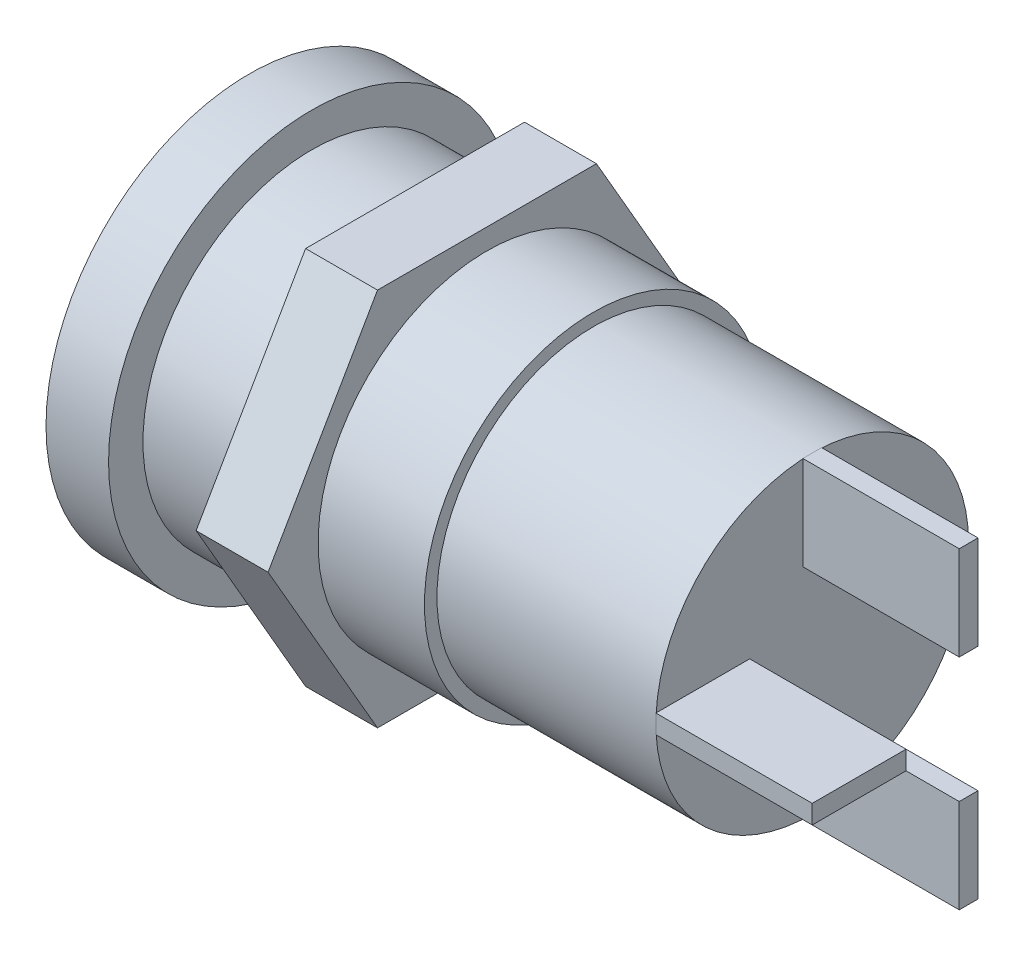
SolidWorks part; units mm, degrees
ref_plane "Front Plane" through (0, 0, 0) normal (0, 0, 1) x (1, 0, 0)
ref_plane "Top Plane" through (0, 0, 0) normal (0, 1, 0) x (1, 0, 0)
ref_plane "Right Plane" through (0, 0, 0) normal (1, 0, 0) x (0, 0, -1)
sketch "SK Front collar" plane through (0, 0, 0) normal (1, 0, 0) x (0, 0, -1)
  circle A0 centre (0, 0) radius 6.5
  circle A1 centre (0, 0) radius 2.9
extrude "Front collar" add sketch "SK Front collar" along normal blind 2 from offset 2 separate body
sketch "SK Centre pin" plane through (0, 0, 0) normal (1, 0, 0) x (0, 0, -1)
  circle A0 centre (0, 0) radius 1.05
extrude "Centre pin" add sketch "SK Centre pin" along normal blind 10.6 from offset 1.6 separate body
sketch "SK Threaded body" plane through (0, 0, 0) normal (1, 0, 0) x (0, 0, -1)
  circle A0 centre (0, 0) radius 5.4
  circle A1 centre (0, 0) radius 2.9
extrude "Threaded body" add sketch "SK Threaded body" along normal blind 9 separate body
sketch "SK Panel nut" plane through (0, 0, 0) normal (1, 0, 0) x (0, 0, -1)
  line L1 (7, 0) -> (3.5, 6.0622)
  line L2 (3.5, 6.0622) -> (-3.5, 6.0622)
  line L3 (-3.5, 6.0622) -> (-7, 0)
  line L4 (-7, 0) -> (-3.5, -6.0622)
  line L5 (-3.5, -6.0622) -> (3.5, -6.0622)
  line L6 (3.5, -6.0622) -> (7, 0)
  circle A0 centre (0, 0) radius 5.4
  circle A1 centre (0, 0) radius 6.0622 construction
extrude "Panel nut" add sketch "SK Panel nut" along normal blind 2.3 from offset 3.3 separate body
sketch "SK Rear housing" plane through (0, 0, 0) normal (1, 0, 0) x (0, 0, -1)
  circle A0 centre (0, 0) radius 5
extrude "Rear housing" add sketch "SK Rear housing" along normal blind 7 from offset 9 separate body
sketch "SK Solder tabs" plane through (0, 0, 0) normal (1, 0, 0) x (0, 0, -1)
  line L1 (0.3, 2) -> (-0.3, 2)
  line L2 (0.3, 2) -> (0.3, 5)
  line L3 (0.3, 5) -> (-0.3, 5)
  line L4 (-0.3, 2) -> (-0.3, 5)
  line L6 (0.3, -5) -> (-0.3, -5)
  line L7 (0.3, -5) -> (0.3, -2)
  line L8 (0.3, -2) -> (-0.3, -2)
  line L9 (-0.3, -5) -> (-0.3, -2)
  line L11 (-2, -0.3) -> (-5, -0.3)
  line L12 (-2, -0.3) -> (-2, 0.3)
  line L13 (-2, 0.3) -> (-5, 0.3)
  line L14 (-5, -0.3) -> (-5, 0.3)
extrude "Solder tabs" add sketch "SK Solder tabs" along normal blind 5 from offset 16 separate body
